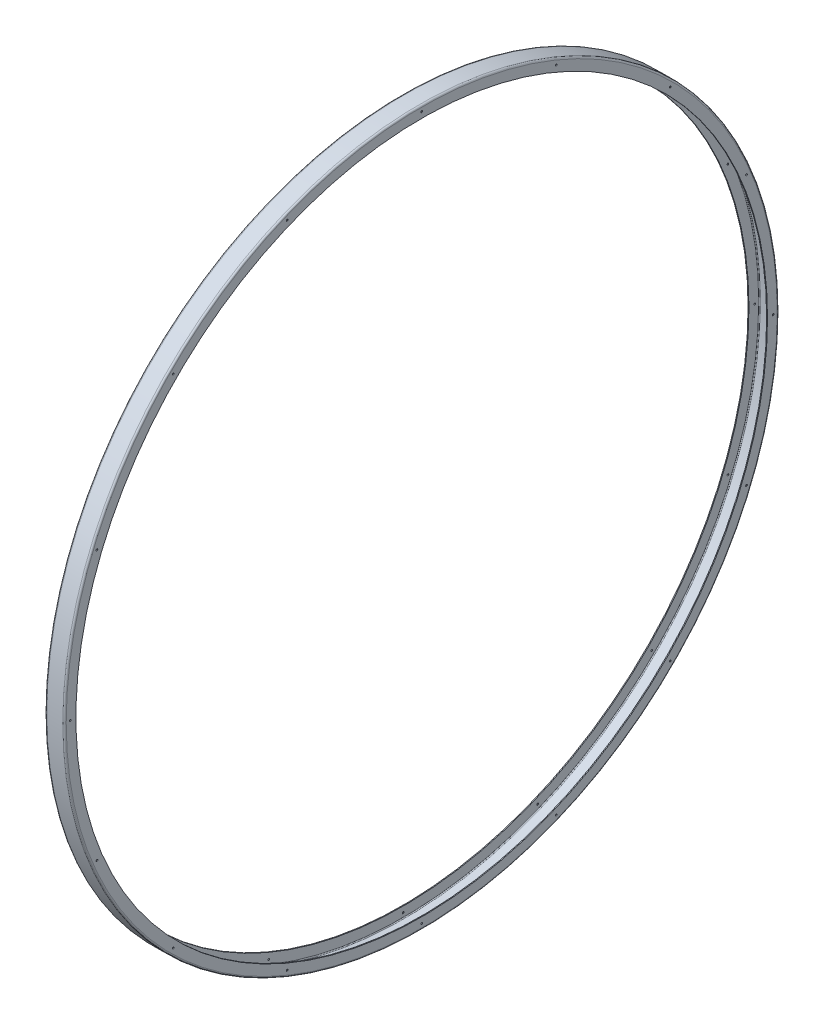
SolidWorks part; units mm, degrees
material "ASTM A36 Steel"
ref_plane "Front Plane" through (0, 0, 0) normal (0, 0, 1) x (1, 0, 0)
ref_plane "Top Plane" through (0, 0, 0) normal (0, 1, 0) x (1, 0, 0)
ref_plane "Right Plane" through (0, 0, 0) normal (1, 0, 0) x (0, 0, -1)
sketch "Sketch1" plane through (0, 0, 0) normal (0, 1, 0) x (1, 0, 0)
  line L0 (11.5152, 34) -> (-44.4848, 34)
  line L1 (-50.4848, 28) -> (-50.4848, -6)
  line L2 (17.5152, 28) -> (17.5152, -6)
  line L3 (-47.4848, 28) -> (-47.4848, -6)
  line L4 (11.5152, 31) -> (-44.4848, 31)
  line L5 (14.5152, 28) -> (14.5152, -6)
  line L6 (17.5152, -6) -> (14.5152, -6)
  line L7 (-47.4848, -6) -> (-50.4848, -6)
  line L9 (-31.365, -1216) -> (-485.7271, -1216) construction
  arc A0 (-44.4848, 34) -> (-50.4848, 28) centre (-44.4848, 28) ccw
  arc A1 (11.5152, 34) -> (17.5152, 28) centre (11.5152, 28) cw
  arc A2 (-44.4848, 31) -> (-47.4848, 28) centre (-44.4848, 28) ccw
  arc A3 (11.5152, 31) -> (14.5152, 28) centre (11.5152, 28) cw
  point P6 (-50.4848, 34)
  point P9 (17.5152, 34)
  dimension "D4" = 6
  dimension "D1" = 68
  dimension "D2" = 40
  dimension "D3" = 40
  dimension "D5" = 3
revolve "Revolve1" add sketch "Sketch1" angle 360 about L9
sketch "Sketch2" plane through (17.5152, 0, 0) normal (1, 0, 0) x (0, 0, -1)
  circle A1 centre (14, 0) radius 3
  dimension "D2" = 6
extrude "Cut-Extrude1" cut sketch "Sketch2" against normal through all both and the other way through all
pattern_circular "CirPattern1" count 16 over 360 about axis through (0, 0, 1216) along (1, 0, 0) of "Cut-Extrude1"
sketch "Sketch3" plane through (-50.4848, 0, 0) normal (-1, 0, 0) x (0, 0, 1)
  line L0 (1216, 1210) -> (1216, 1250)
  circle A0 centre (1216, 0) radius 1210 construction
  circle A1 centre (1216, 0) radius 1250 construction
